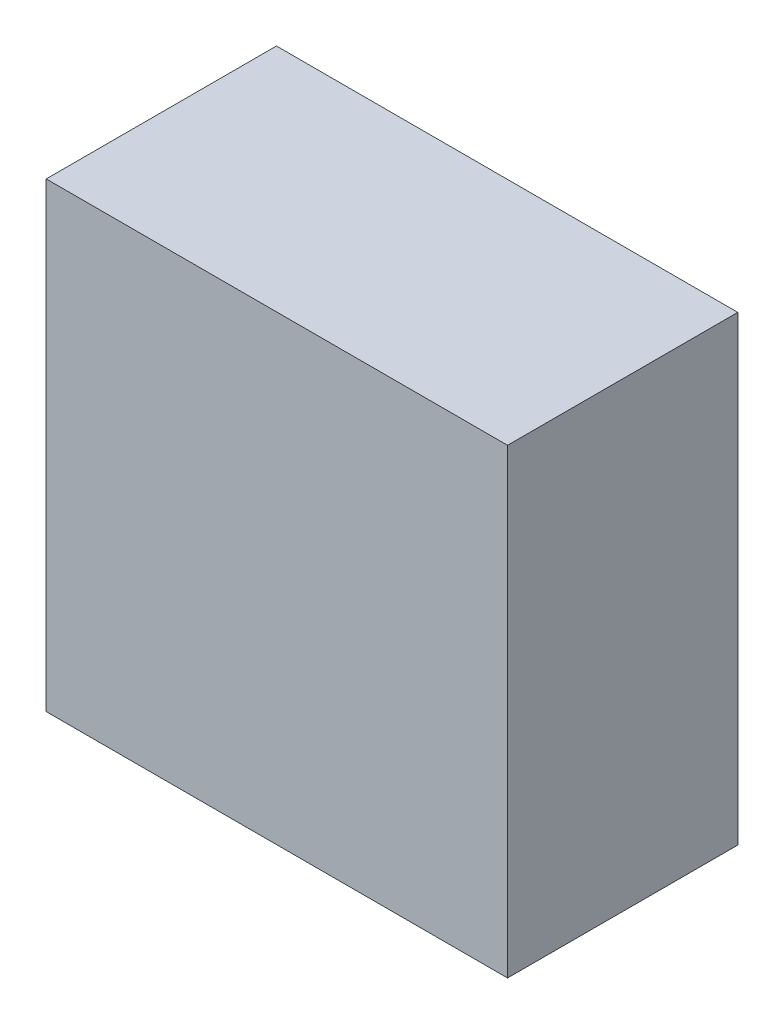
SolidWorks part; units mm, degrees
ref_plane "Front Plane" through (0, 0, 0) normal (0, 0, 1) x (1, 0, 0)
ref_plane "Top Plane" through (0, 0, 0) normal (0, 1, 0) x (1, 0, 0)
ref_plane "Right Plane" through (0, 0, 0) normal (1, 0, 0) x (0, 0, -1)
sketch "Sketch1" plane through (0, 0, 0) normal (0, 0, 1) x (1, 0, 0)
  line L1 (50.1, 50.1) -> (-50.1, 50.1)
  line L2 (50.1, 50.1) -> (50.1, -50.1)
  line L3 (50.1, -50.1) -> (-50.1, -50.1)
  line L4 (-50.1, 50.1) -> (-50.1, -50.1)
  line L5 (0, -50.1) -> (0, 50.1) construction
  line L6 (50.1, 0) -> (-50.1, 0) construction
  circle A0 centre (0, 0) radius 45.1 construction
  point P0 (0, 0)
  dimension "D1" = 90.2
  dimension "D2" = 5
extrude "Boss-Extrude1" add sketch "Sketch1" against normal blind 50
